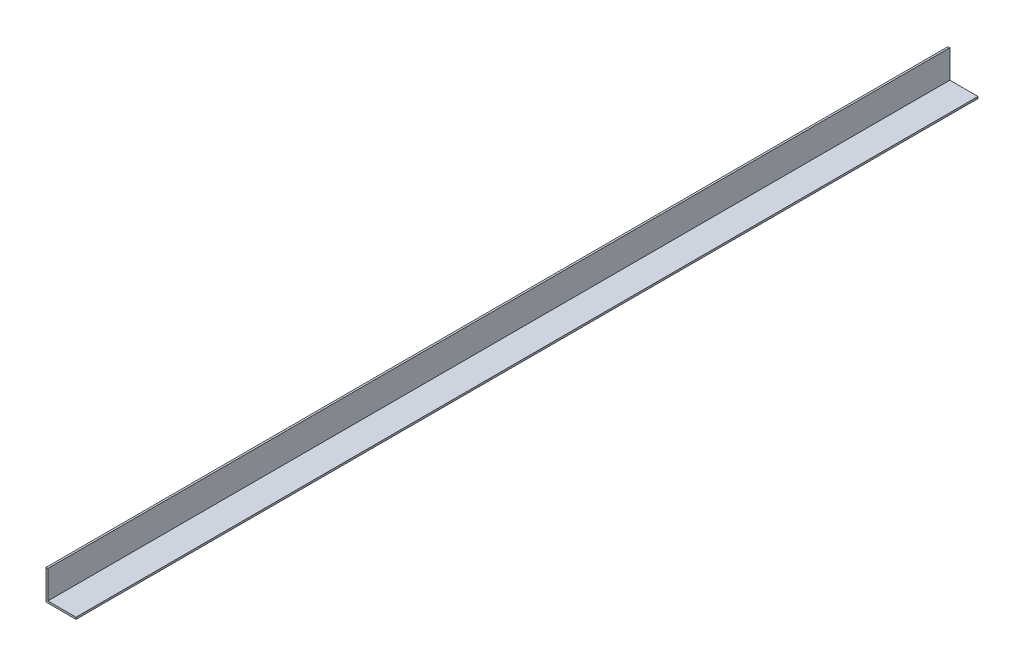
SolidWorks part; units mm, degrees
material "ASTM A36 Acero"
ref_plane "Alzado" through (0, 0, 0) normal (0, 0, 1) x (1, 0, 0)
ref_plane "Planta" through (0, 0, 0) normal (0, 1, 0) x (1, 0, 0)
ref_plane "Vista lateral" through (0, 0, 0) normal (1, 0, 0) x (0, 0, -1)
sketch "Croquis1" plane through (0, 0, 0) normal (0, 0, 1) x (1, 0, 0)
  line L0 (0, 203) -> (0, 0)
  line L1 (0, 0) -> (203, 0)
  line L2 (203, 0) -> (203, 12.7)
  line L3 (203, 12.7) -> (12.7, 12.7)
  line L4 (12.7, 12.7) -> (12.7, 203)
  line L5 (12.7, 203) -> (0, 203)
  dimension "D1" = 12.7
  dimension "D2" = 203
extrude "Saliente-Extruir1" add sketch "Croquis1" against normal blind 6100
